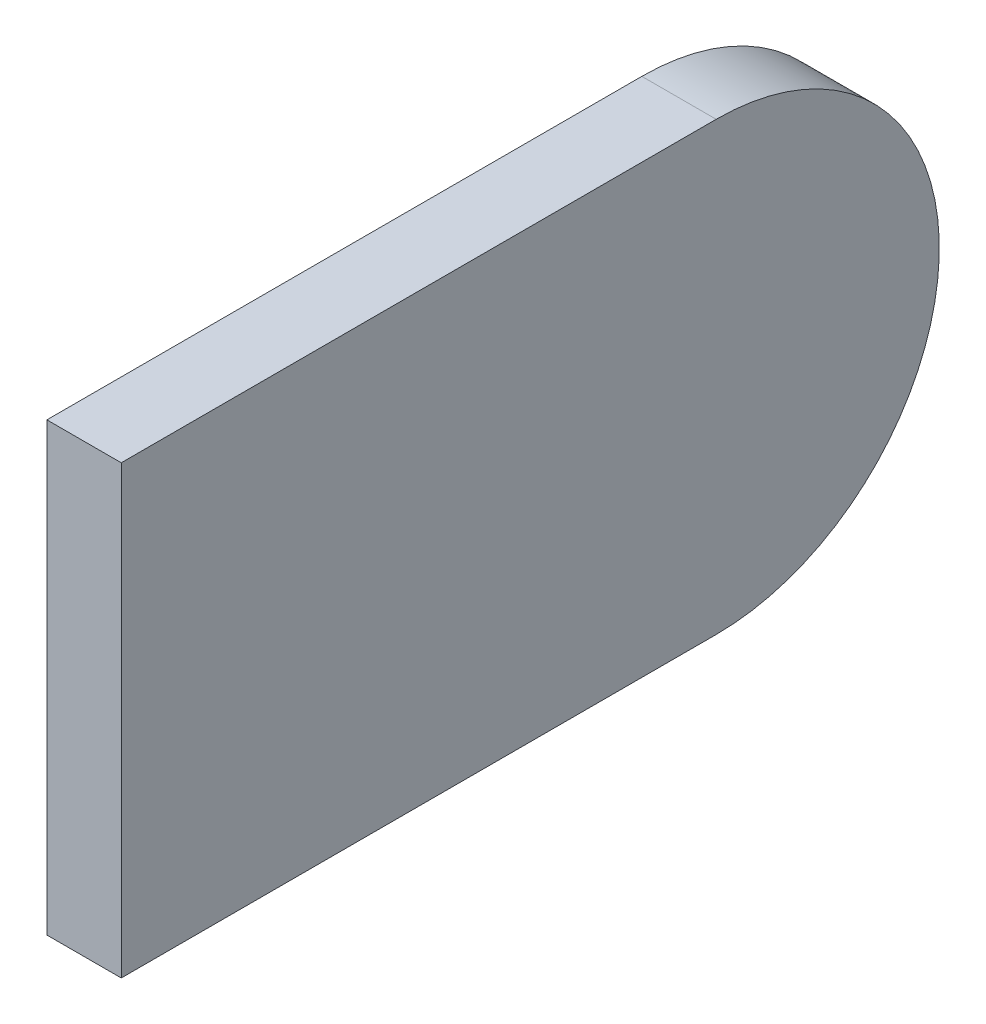
SolidWorks part; units mm, degrees
material "Plain Carbon Steel"
ref_plane "Front Plane" through (0, 0, 0) normal (0, 0, 1) x (1, 0, 0)
ref_plane "Top Plane" through (0, 0, 0) normal (0, 1, 0) x (1, 0, 0)
ref_plane "Right Plane" through (0, 0, 0) normal (1, 0, 0) x (0, 0, -1)
sketch "Sketch2" plane through (0, 0, 0) normal (1, 0, 0) x (0, 0, -1)
  line L0 (0, 0) -> (80, 0)
  line L1 (80, 60) -> (0, 60)
  line L2 (0, 60) -> (0, 0)
  arc A0 (80, 0) -> (80, 60) centre (80, 30) ccw
  dimension "D2" = 30
  dimension "D1" = 80
extrude "Boss-Extrude1" add sketch "Sketch2" along normal blind 10
